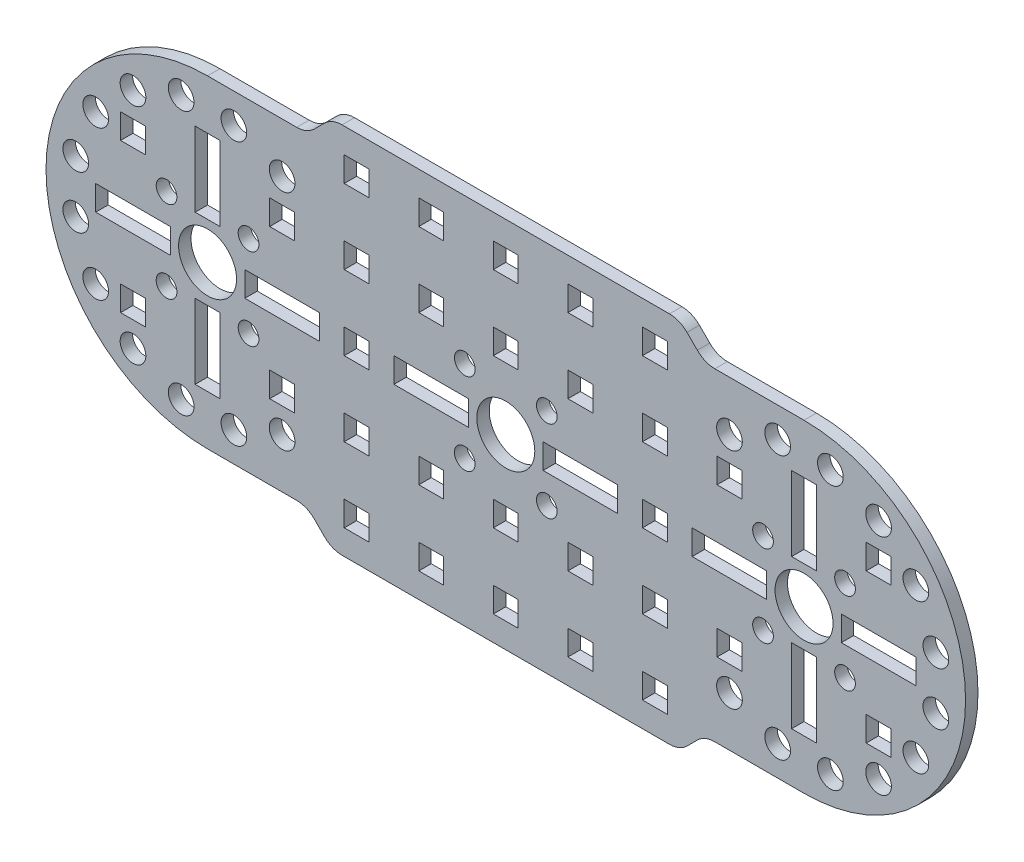
SolidWorks part; units mm, degrees
ref_plane "Alzado" through (0, 0, 0) normal (0, 0, 1) x (1, 0, 0)
ref_plane "Planta" through (0, 0, 0) normal (0, 1, 0) x (1, 0, 0)
ref_plane "Vista lateral" through (0, 0, 0) normal (1, 0, 0) x (0, 0, -1)
sketch "Model" plane through (0, 0, 0) normal (0, 0, 1) x (1, 0, 0)
  line L0 (31.8977, 276.6454) -> (40.8977, 276.6454)
  line L1 (31.8977, 279.6454) -> (31.8977, 276.6454)
  line L2 (40.8977, 279.6454) -> (31.8977, 279.6454)
  line L3 (40.8977, 276.6454) -> (40.8977, 279.6454)
  line L4 (28.8977, 282.6454) -> (28.8977, 291.6454)
  line L5 (25.8977, 282.6454) -> (28.8977, 282.6454)
  line L6 (25.8977, 291.6454) -> (25.8977, 282.6454)
  line L7 (28.8977, 291.6454) -> (25.8977, 291.6454)
  line L8 (22.8977, 279.6454) -> (13.8977, 279.6454)
  line L9 (22.8977, 276.6454) -> (22.8977, 279.6454)
  line L10 (13.8977, 276.6454) -> (22.8977, 276.6454)
  line L11 (13.8977, 279.6454) -> (13.8977, 276.6454)
  line L12 (25.8977, 273.6454) -> (25.8977, 264.6454)
  line L13 (28.8977, 273.6454) -> (25.8977, 273.6454)
  line L14 (28.8977, 264.6454) -> (28.8977, 273.6454)
  line L15 (25.8977, 264.6454) -> (28.8977, 264.6454)
  line L16 (103.8977, 276.6454) -> (112.8977, 276.6454)
  line L17 (103.8977, 279.6454) -> (103.8977, 276.6454)
  line L18 (112.8977, 279.6454) -> (103.8977, 279.6454)
  line L19 (112.8977, 276.6454) -> (112.8977, 279.6454)
  line L20 (100.8977, 282.6454) -> (100.8977, 291.6454)
  line L21 (97.8977, 282.6454) -> (100.8977, 282.6454)
  line L22 (97.8977, 291.6454) -> (97.8977, 282.6454)
  line L23 (100.8977, 291.6454) -> (97.8977, 291.6454)
  line L24 (94.8977, 279.6454) -> (85.8977, 279.6454)
  line L25 (94.8977, 276.6454) -> (94.8977, 279.6454)
  line L26 (85.8977, 276.6454) -> (94.8977, 276.6454)
  line L27 (85.8977, 279.6454) -> (85.8977, 276.6454)
  line L28 (97.8977, 273.6454) -> (97.8977, 264.6454)
  line L29 (100.8977, 273.6454) -> (97.8977, 273.6454)
  line L30 (100.8977, 264.6454) -> (100.8977, 273.6454)
  line L31 (97.8977, 264.6454) -> (100.8977, 264.6454)
  line L32 (67.8977, 276.6454) -> (76.8977, 276.6454)
  line L33 (67.8977, 279.6454) -> (67.8977, 276.6454)
  line L34 (76.8977, 279.6454) -> (67.8977, 279.6454)
  line L35 (76.8977, 276.6454) -> (76.8977, 279.6454)
  line L36 (58.8977, 279.6454) -> (49.8977, 279.6454)
  line L37 (58.8977, 276.6454) -> (58.8977, 279.6454)
  line L38 (49.8977, 276.6454) -> (58.8977, 276.6454)
  line L39 (49.8977, 279.6454) -> (49.8977, 276.6454)
  line L40 (16.8977, 288.6454) -> (16.8977, 285.6454)
  line L41 (19.8977, 288.6454) -> (16.8977, 288.6454)
  line L42 (19.8977, 285.6454) -> (19.8977, 288.6454)
  line L43 (16.8977, 285.6454) -> (19.8977, 285.6454)
  line L44 (34.8977, 270.6454) -> (34.8977, 267.6454)
  line L45 (37.8977, 270.6454) -> (34.8977, 270.6454)
  line L46 (37.8977, 267.6454) -> (37.8977, 270.6454)
  line L47 (34.8977, 267.6454) -> (37.8977, 267.6454)
  line L48 (88.8977, 288.6454) -> (88.8977, 285.6454)
  line L49 (91.8977, 288.6454) -> (88.8977, 288.6454)
  line L50 (91.8977, 285.6454) -> (91.8977, 288.6454)
  line L51 (88.8977, 285.6454) -> (91.8977, 285.6454)
  line L52 (34.8977, 288.6454) -> (34.8977, 285.6454)
  line L53 (37.8977, 288.6454) -> (34.8977, 288.6454)
  line L54 (37.8977, 285.6454) -> (37.8977, 288.6454)
  line L55 (34.8977, 285.6454) -> (37.8977, 285.6454)
  line L56 (43.8977, 261.6454) -> (43.8977, 258.6454)
  line L57 (46.8977, 261.6454) -> (43.8977, 261.6454)
  line L58 (46.8977, 258.6454) -> (46.8977, 261.6454)
  line L59 (43.8977, 258.6454) -> (46.8977, 258.6454)
  line L60 (79.8977, 261.6454) -> (79.8977, 258.6454)
  line L61 (82.8977, 261.6454) -> (79.8977, 261.6454)
  line L62 (82.8977, 258.6454) -> (82.8977, 261.6454)
  line L63 (79.8977, 258.6454) -> (82.8977, 258.6454)
  line L64 (16.8977, 270.6454) -> (16.8977, 267.6454)
  line L65 (19.8977, 270.6454) -> (16.8977, 270.6454)
  line L66 (19.8977, 267.6454) -> (19.8977, 270.6454)
  line L67 (16.8977, 267.6454) -> (19.8977, 267.6454)
  line L68 (43.8977, 279.6454) -> (43.8977, 276.6454)
  line L69 (46.8977, 279.6454) -> (43.8977, 279.6454)
  line L70 (46.8977, 276.6454) -> (46.8977, 279.6454)
  line L71 (43.8977, 276.6454) -> (46.8977, 276.6454)
  line L72 (106.8977, 288.6454) -> (106.8977, 285.6454)
  line L73 (109.8977, 288.6454) -> (106.8977, 288.6454)
  line L74 (109.8977, 285.6454) -> (109.8977, 288.6454)
  line L75 (106.8977, 285.6454) -> (109.8977, 285.6454)
  line L76 (88.8977, 270.6454) -> (88.8977, 267.6454)
  line L77 (91.8977, 270.6454) -> (88.8977, 270.6454)
  line L78 (91.8977, 267.6454) -> (91.8977, 270.6454)
  line L79 (88.8977, 267.6454) -> (91.8977, 267.6454)
  line L80 (79.8977, 279.6454) -> (79.8977, 276.6454)
  line L81 (82.8977, 279.6454) -> (79.8977, 279.6454)
  line L82 (82.8977, 276.6454) -> (82.8977, 279.6454)
  line L83 (79.8977, 276.6454) -> (82.8977, 276.6454)
  line L84 (106.8977, 270.6454) -> (106.8977, 267.6454)
  line L85 (109.8977, 270.6454) -> (106.8977, 270.6454)
  line L86 (109.8977, 267.6454) -> (109.8977, 270.6454)
  line L87 (106.8977, 267.6454) -> (109.8977, 267.6454)
  line L88 (52.8977, 261.6454) -> (52.8977, 258.6454)
  line L89 (55.8977, 261.6454) -> (52.8977, 261.6454)
  line L90 (55.8977, 258.6454) -> (55.8977, 261.6454)
  line L91 (52.8977, 258.6454) -> (55.8977, 258.6454)
  line L92 (61.8977, 261.6454) -> (61.8977, 258.6454)
  line L93 (64.8977, 261.6454) -> (61.8977, 261.6454)
  line L94 (64.8977, 258.6454) -> (64.8977, 261.6454)
  line L95 (61.8977, 258.6454) -> (64.8977, 258.6454)
  line L96 (70.8977, 261.6454) -> (70.8977, 258.6454)
  line L97 (73.8977, 261.6454) -> (70.8977, 261.6454)
  line L98 (73.8977, 258.6454) -> (73.8977, 261.6454)
  line L99 (70.8977, 258.6454) -> (73.8977, 258.6454)
  line L100 (43.8977, 270.6454) -> (43.8977, 267.6454)
  line L101 (46.8977, 270.6454) -> (43.8977, 270.6454)
  line L102 (46.8977, 267.6454) -> (46.8977, 270.6454)
  line L103 (43.8977, 267.6454) -> (46.8977, 267.6454)
  line L104 (79.8977, 270.6454) -> (79.8977, 267.6454)
  line L105 (82.8977, 270.6454) -> (79.8977, 270.6454)
  line L106 (82.8977, 267.6454) -> (82.8977, 270.6454)
  line L107 (79.8977, 267.6454) -> (82.8977, 267.6454)
  line L108 (52.8977, 270.6454) -> (52.8977, 267.6454)
  line L109 (55.8977, 270.6454) -> (52.8977, 270.6454)
  line L110 (55.8977, 267.6454) -> (55.8977, 270.6454)
  line L111 (52.8977, 267.6454) -> (55.8977, 267.6454)
  line L112 (61.8977, 270.6454) -> (61.8977, 267.6454)
  line L113 (64.8977, 270.6454) -> (61.8977, 270.6454)
  line L114 (64.8977, 267.6454) -> (64.8977, 270.6454)
  line L115 (61.8977, 267.6454) -> (64.8977, 267.6454)
  line L116 (70.8977, 270.6454) -> (70.8977, 267.6454)
  line L117 (73.8977, 270.6454) -> (70.8977, 270.6454)
  line L118 (73.8977, 267.6454) -> (73.8977, 270.6454)
  line L119 (70.8977, 267.6454) -> (73.8977, 267.6454)
  line L120 (43.8977, 288.6454) -> (43.8977, 285.6454)
  line L121 (46.8977, 288.6454) -> (43.8977, 288.6454)
  line L122 (46.8977, 285.6454) -> (46.8977, 288.6454)
  line L123 (43.8977, 285.6454) -> (46.8977, 285.6454)
  line L124 (79.8977, 288.6454) -> (79.8977, 285.6454)
  line L125 (82.8977, 288.6454) -> (79.8977, 288.6454)
  line L126 (82.8977, 285.6454) -> (82.8977, 288.6454)
  line L127 (79.8977, 285.6454) -> (82.8977, 285.6454)
  line L128 (52.8977, 288.6454) -> (52.8977, 285.6454)
  line L129 (55.8977, 288.6454) -> (52.8977, 288.6454)
  line L130 (55.8977, 285.6454) -> (55.8977, 288.6454)
  line L131 (52.8977, 285.6454) -> (55.8977, 285.6454)
  line L132 (61.8977, 288.6454) -> (61.8977, 285.6454)
  line L133 (64.8977, 288.6454) -> (61.8977, 288.6454)
  line L134 (64.8977, 285.6454) -> (64.8977, 288.6454)
  line L135 (61.8977, 285.6454) -> (64.8977, 285.6454)
  line L136 (70.8977, 288.6454) -> (70.8977, 285.6454)
  line L137 (73.8977, 288.6454) -> (70.8977, 288.6454)
  line L138 (73.8977, 285.6454) -> (73.8977, 288.6454)
  line L139 (70.8977, 285.6454) -> (73.8977, 285.6454)
  line L140 (43.8977, 297.6454) -> (43.8977, 294.6454)
  line L141 (46.8977, 297.6454) -> (43.8977, 297.6454)
  line L142 (46.8977, 294.6454) -> (46.8977, 297.6454)
  line L143 (43.8977, 294.6454) -> (46.8977, 294.6454)
  line L144 (79.8977, 297.6454) -> (79.8977, 294.6454)
  line L145 (82.8977, 297.6454) -> (79.8977, 297.6454)
  line L146 (82.8977, 294.6454) -> (82.8977, 297.6454)
  line L147 (79.8977, 294.6454) -> (82.8977, 294.6454)
  line L148 (52.8977, 297.6454) -> (52.8977, 294.6454)
  line L149 (55.8977, 297.6454) -> (52.8977, 297.6454)
  line L150 (55.8977, 294.6454) -> (55.8977, 297.6454)
  line L151 (52.8977, 294.6454) -> (55.8977, 294.6454)
  line L152 (61.8977, 297.6454) -> (61.8977, 294.6454)
  line L153 (64.8977, 297.6454) -> (61.8977, 297.6454)
  line L154 (64.8977, 294.6454) -> (64.8977, 297.6454)
  line L155 (61.8977, 294.6454) -> (64.8977, 294.6454)
  line L156 (70.8977, 297.6454) -> (70.8977, 294.6454)
  line L157 (73.8977, 297.6454) -> (70.8977, 297.6454)
  line L158 (73.8977, 294.6454) -> (73.8977, 297.6454)
  line L159 (70.8977, 294.6454) -> (73.8977, 294.6454)
  line L160 (43.6403, 300.6454) -> (83.155, 300.6454)
  line L162 (27.3977, 297.6454) -> (38.155, 297.6454)
  line L163 (99.3977, 297.6454) -> (88.6403, 297.6454)
  line L164 (40.2763, 298.524) -> (41.519, 299.7667)
  line L165 (86.519, 298.524) -> (85.2763, 299.7667)
  line L166 (43.6403, 255.6454) -> (83.155, 255.6454)
  line L168 (27.3977, 258.6454) -> (38.155, 258.6454)
  line L169 (99.3977, 258.6454) -> (88.6403, 258.6454)
  line L170 (40.2763, 257.7667) -> (41.519, 256.524)
  line L171 (86.519, 257.7667) -> (85.2763, 256.524)
  circle A0 centre (22.4479, 283.0951) radius 1.25
  circle A1 centre (22.4479, 273.1956) radius 1.25
  circle A2 centre (32.3474, 273.1956) radius 1.25
  circle A3 centre (32.3474, 283.0951) radius 1.25
  circle A4 centre (27.3977, 278.1454) radius 3.5
  circle A5 centre (18.3977, 291.6454) radius 1.55
  circle A6 centre (18.3977, 264.6454) radius 1.55
  circle A7 centre (36.3977, 291.6454) radius 1.55
  circle A8 centre (36.3977, 264.6454) radius 1.55
  circle A9 centre (13.8977, 269.1454) radius 1.55
  circle A10 centre (13.8977, 287.1454) radius 1.55
  circle A11 centre (30.5796, 294.0553) radius 1.55
  circle A12 centre (24.2157, 262.2355) radius 1.55
  circle A13 centre (30.5796, 262.2355) radius 1.55
  circle A14 centre (24.2157, 294.0553) radius 1.55
  circle A15 centre (11.4878, 281.3273) radius 1.55
  circle A16 centre (11.4878, 274.9634) radius 1.55
  circle A17 centre (94.4479, 283.0951) radius 1.25
  circle A18 centre (94.4479, 273.1956) radius 1.25
  circle A19 centre (104.3474, 273.1956) radius 1.25
  circle A20 centre (104.3474, 283.0951) radius 1.25
  circle A21 centre (99.3977, 278.1454) radius 3.5
  circle A22 centre (90.3977, 291.6454) radius 1.55
  circle A23 centre (90.3977, 264.6454) radius 1.55
  circle A24 centre (108.3977, 291.6454) radius 1.55
  circle A25 centre (108.3977, 264.6454) radius 1.55
  circle A26 centre (112.8977, 269.1454) radius 1.55
  circle A27 centre (112.8977, 287.1454) radius 1.55
  circle A28 centre (102.5796, 294.0553) radius 1.55
  circle A29 centre (96.2157, 262.2355) radius 1.55
  circle A30 centre (102.5796, 262.2355) radius 1.55
  circle A31 centre (96.2157, 294.0553) radius 1.55
  circle A32 centre (115.3076, 274.9634) radius 1.55
  circle A33 centre (115.3076, 281.3273) radius 1.55
  circle A34 centre (58.4479, 283.0951) radius 1.25
  circle A35 centre (58.4479, 273.1956) radius 1.25
  circle A36 centre (68.3474, 273.1956) radius 1.25
  circle A37 centre (68.3474, 283.0951) radius 1.25
  circle A38 centre (63.3977, 278.1454) radius 3.5
  arc A39 (27.3977, 297.6454) -> (27.3977, 258.6454) centre (27.3977, 278.1454) ccw
  arc A40 (38.155, 297.6454) -> (40.2763, 298.524) centre (38.155, 300.6454) ccw
  arc A41 (86.519, 298.524) -> (88.6403, 297.6454) centre (88.6403, 300.6454) ccw
  arc A42 (99.3977, 258.6454) -> (99.3977, 297.6454) centre (99.3977, 278.1454) ccw
  arc A43 (43.6403, 300.6454) -> (41.519, 299.7667) centre (43.6403, 297.6454) ccw
  arc A44 (85.2763, 299.7667) -> (83.155, 300.6454) centre (83.155, 297.6454) ccw
  arc A45 (40.2763, 257.7667) -> (38.155, 258.6454) centre (38.155, 255.6454) ccw
  arc A46 (88.6403, 258.6454) -> (86.519, 257.7667) centre (88.6403, 255.6454) ccw
  arc A47 (41.519, 256.524) -> (43.6403, 255.6454) centre (43.6403, 258.6454) ccw
  arc A48 (83.155, 255.6454) -> (85.2763, 256.524) centre (83.155, 258.6454) ccw
extrude "Saliente-Extruir1" add sketch "Model" along normal blind 1.5
